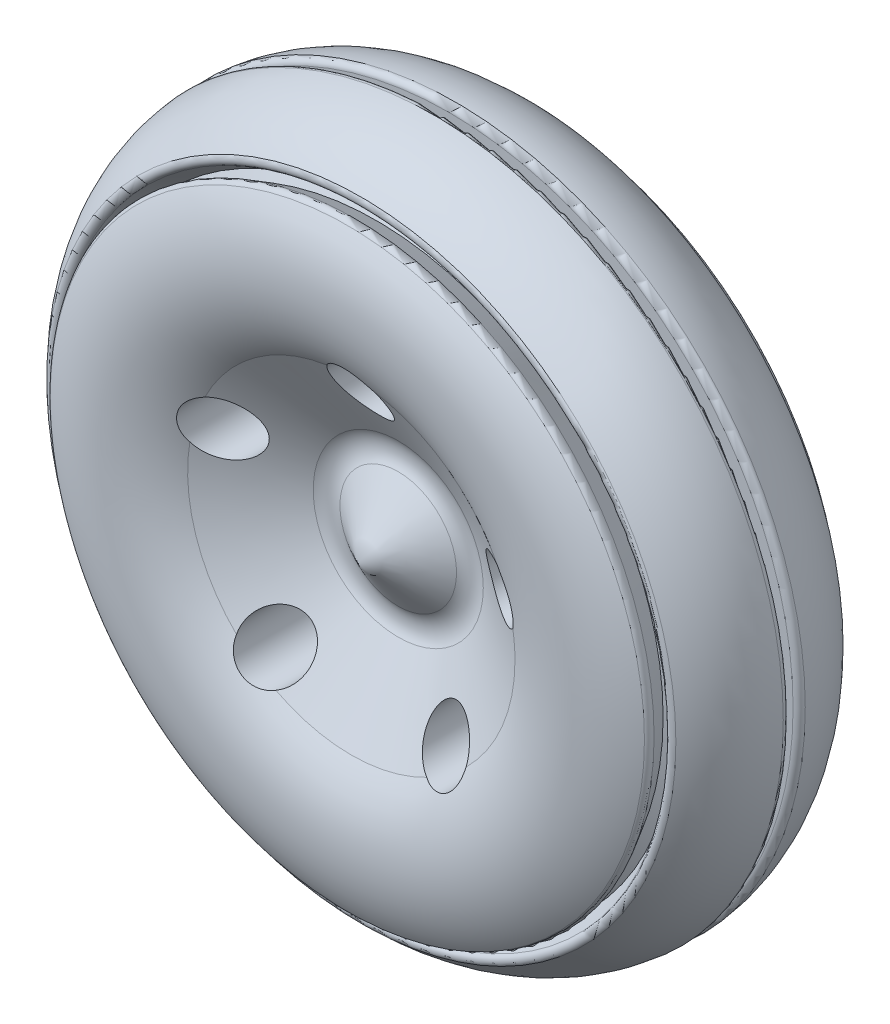
SolidWorks part; units mm, degrees
ref_plane "Front Plane" through (0, 0, 0) normal (0, 0, 1) x (1, 0, 0)
ref_plane "Top Plane" through (0, 0, 0) normal (0, 1, 0) x (1, 0, 0)
ref_plane "Right Plane" through (0, 0, 0) normal (1, 0, 0) x (0, 0, -1)
sketch "Sketch1" plane through (0, 0, 0) normal (1, 0, 0) x (0, 0, -1)
  line L0 (-37.5, 0) -> (37.5, 0)
  line L1 (0, 129.8507) -> (0, -39.7166) construction
  line L2 (37.5, 0) -> (20, 24.9926)
  line L3 (20, 36.4641) -> (40.1218, 70.1631)
  line L6 (-0.0213, 135) -> (1.9787, 135)
  line L7 (1.9787, 147.2884) -> (1.9787, 135)
  line L8 (35.2975, 130.9562) -> (27.3449, 126.3647)
  line L10 (27.3449, 126.3647) -> (29.3449, 122.9006)
  line L11 (38.4916, 128.1815) -> (29.3449, 122.9006)
  line L12 (-1.9787, 147.2884) -> (-1.9787, 135)
  line L13 (0.0213, 135) -> (-1.9787, 135)
  line L14 (-35.2975, 130.9562) -> (-27.3449, 126.3647)
  line L15 (-27.3449, 126.3647) -> (-29.3449, 122.9006)
  line L16 (-38.4916, 128.1815) -> (-29.3449, 122.9006)
  line L17 (-20, 36.4641) -> (-40.1218, 70.1631)
  line L18 (-37.5, 0) -> (-20, 24.9926)
  arc A0 (40.1218, 70.1631) -> (41.8333, 127.3857) centre (0, 100) ccw
  arc A1 (1.9787, 147.2884) -> (4.7145, 149.7772) centre (4.4787, 147.2884) cw
  arc A2 (20, 24.9926) -> (20, 36.4641) centre (28.1915, 30.7284) cw
  arc A3 (35.8395, 134.8645) -> (4.7145, 149.7772) centre (0, 100) ccw
  arc A4 (35.8395, 134.8645) -> (35.2975, 130.9562) centre (34.0475, 133.1212) cw
  arc A5 (41.8333, 127.3857) -> (38.4916, 128.1815) centre (39.7416, 126.0164) ccw
  arc A6 (-1.9787, 147.2884) -> (-4.7145, 149.7772) centre (-4.4787, 147.2884) ccw
  arc A7 (-35.8395, 134.8645) -> (-4.7145, 149.7772) centre (0, 100) cw
  arc A8 (-35.8395, 134.8645) -> (-35.2975, 130.9562) centre (-34.0475, 133.1212) ccw
  arc A9 (-41.8333, 127.3857) -> (-38.4916, 128.1815) centre (-39.7416, 126.0164) cw
  arc A10 (-40.1218, 70.1631) -> (-41.8333, 127.3857) centre (0, 100) cw
  arc A11 (-20, 24.9926) -> (-20, 36.4641) centre (-28.1915, 30.7284) ccw
  point P25 (37.9884, 132.5097)
  point P46 (0, 0)
  dimension "D1" = 100
  dimension "D8" = 2.5
  dimension "D9" = 60
  dimension "D12" = 2.5
  dimension "D13" = 2.5
  dimension "D14" = 10
  dimension "D2" = 37.5
  dimension "D3" = 55
  dimension "D4" = 100
  dimension "D5" = 20
  dimension "D6" = 35
  dimension "D7" = 2
  dimension "D10" = 4
  dimension "D11" = 12.29
revolve "Revolve1" add sketch "Sketch1" angle 360 about L0
sketch "Sketch3" plane through (0, 0, 0) normal (0, 0, 1) x (1, 0, 0)
  circle A0 centre (0, 0) radius 62.5 construction
  circle A1 centre (0, 62.5) radius 12.5
  circle A2 centre (59.441, 19.3136) radius 12.5
  circle A3 centre (36.7366, -50.5636) radius 12.5
  circle A4 centre (-36.7366, -50.5636) radius 12.5
  circle A5 centre (-59.441, 19.3136) radius 12.5
  dimension "D1" = 5
extrude "Cut-Extrude1" cut sketch "Sketch3" against normal through all both and the other way through all
